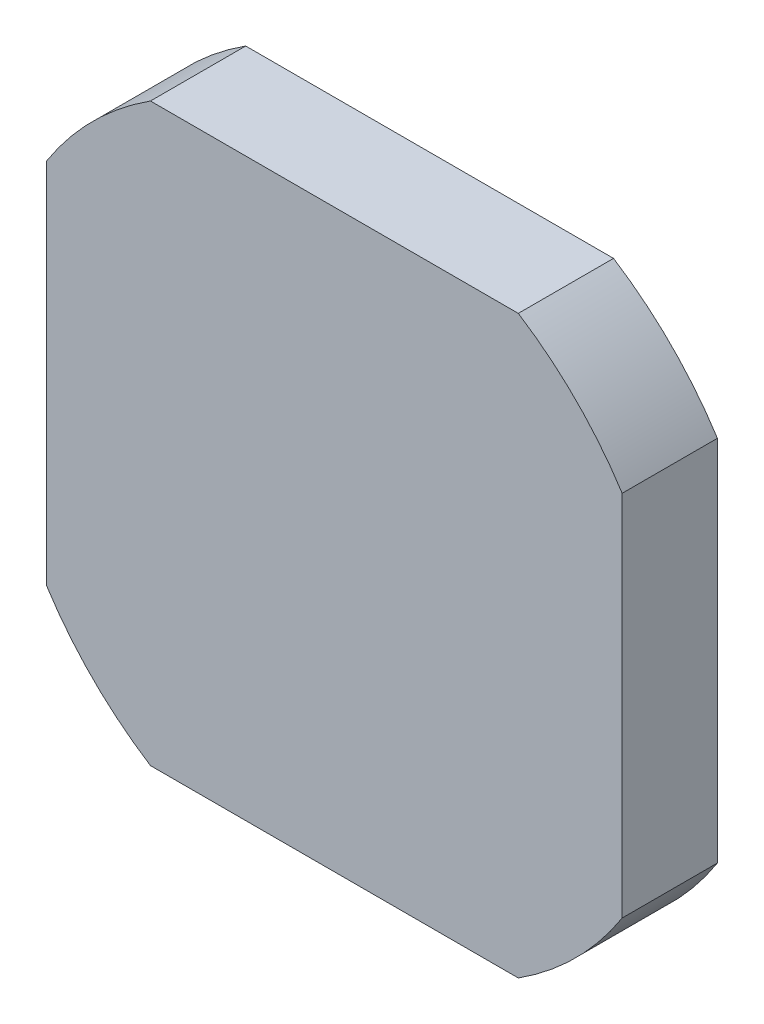
SolidWorks part; units mm, degrees
material "Acero aleado"
ref_plane "Alzado" through (0, 0, 0) normal (0, 0, 1) x (1, 0, 0)
ref_plane "Planta" through (0, 0, 0) normal (0, 1, 0) x (1, 0, 0)
ref_plane "Vista lateral" through (0, 0, 0) normal (1, 0, 0) x (0, 0, -1)
other "Исполнения"
sketch "Croquis1" plane through (0, 0, 0) normal (0, 0, 1) x (1, 0, 0)
  line L0 (-17.15, 21.15) -> (-21.15, 17.15)
  line L1 (-17.15, 21.15) -> (17.15, 21.15)
  line L2 (-21.15, 17.15) -> (-21.15, -17.15)
  line L3 (-17.15, -21.15) -> (17.15, -21.15)
  line L4 (21.15, 17.15) -> (21.15, -17.15)
  line L5 (-21.15, 21.15) -> (21.15, -21.15) construction
  line L6 (-21.15, -21.15) -> (21.15, 21.15) construction
  line L7 (17.15, 21.15) -> (21.15, 17.15)
  line L8 (21.15, -17.15) -> (17.15, -21.15)
  line L9 (-21.15, -17.15) -> (-17.15, -21.15)
  point P0 (0, 0)
  dimension "D1" = 42.3
  dimension "D2" = 42.3
extrude "Saliente-Extruir1" add sketch "Croquis1" along normal blind 7
sketch "Эскиз1" plane through (0, 0, 7) normal (0, 0, 1) x (1, 0, 0)
  circle A0 centre (0, 0) radius 25.1
  dimension "D1" = 50.2
extrude "Вырез-Вытянуть1" cut sketch "Эскиз1" against normal through all flip side to cut
